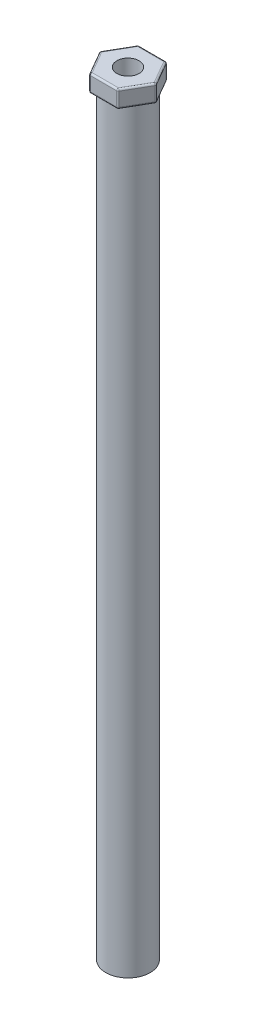
SolidWorks part; units mm, degrees
ref_plane "Front Plane" through (0, 0, 0) normal (0, 0, 1) x (1, 0, 0)
ref_plane "Top Plane" through (0, 0, 0) normal (0, 1, 0) x (1, 0, 0)
ref_plane "Right Plane" through (0, 0, 0) normal (1, 0, 0) x (0, 0, -1)
sketch "Sketch1" plane through (0, 0, 0) normal (0, 1, 0) x (1, 0, 0)
  circle A0 centre (0, 0) radius 6.35
  circle A1 centre (0, 0) radius 3.175
  dimension "D1" = 12.7
extrude "Boss-Extrude1" add sketch "Sketch1" along normal blind 215.9
ref_plane "Plane1" through (0, 107.95, 0) normal (0, 1, 0) x (1, 0, 0)
sketch "Sketch2" plane through (0, 215.9, 0) normal (0, 1, 0) x (1, 0, 0)
  line L1 (-8.0656, 0) -> (-4.0328, -6.985)
  line L2 (-4.0328, -6.985) -> (4.0328, -6.985)
  line L3 (4.0328, -6.985) -> (8.0656, 0)
  line L4 (8.0656, 0) -> (4.0328, 6.985)
  line L5 (4.0328, 6.985) -> (-4.0328, 6.985)
  line L6 (-4.0328, 6.985) -> (-8.0656, 0)
  circle A0 centre (0, 0) radius 6.985 construction
  circle A1 centre (0, 0) radius 3.175
  dimension "D1" = 13.97
extrude "Boss-Extrude2" add sketch "Sketch2" along normal blind 5
fillet "Fillet1" radius 0.5 18 edges at (6.0492, 215.9, -3.4925) (4.0328, 218.4, -6.985) (8.0656, 218.4, 0) (-4.0328, 218.4, -6.985) (-6.0492, 215.9, -3.4925) (-8.0656, 218.4, 0) (-6.0492, 215.9, 3.4925) (-4.0328, 218.4, 6.985) (0, 215.9, 6.985) (6.0492, 215.9, 3.4925) (4.0328, 218.4, 6.985) (6.0492, 220.9, 3.4925) (6.0492, 220.9, -3.4925) (0, 220.9, -6.985) (-6.0492, 220.9, -3.4925) (-6.0492, 220.9, 3.4925) (0, 220.9, 6.985) (0, 215.9, -6.985)
mirror "Mirror1" [suppressed] about plane through (0, 107.95, 0) normal (0, 1, 0)
